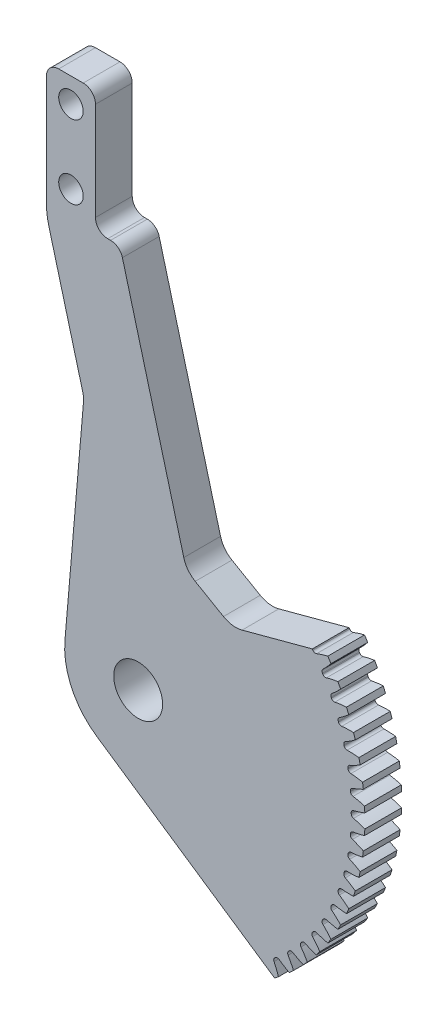
SolidWorks part; units mm, degrees
material "Delrin 2700 NC010, Low Viscosity Acetal Copolymer (SS)"
ref_plane "Front Plane" through (0, 0, 0) normal (0, 0, 1) x (1, 0, 0)
ref_plane "Top Plane" through (0, 0, 0) normal (0, 1, 0) x (1, 0, 0)
ref_plane "Right Plane" through (0, 0, 0) normal (1, 0, 0) x (0, 0, -1)
sketch "Sketch2" plane through (0, 0, 0) normal (0, 0, 1) x (1, 0, 0)
  circle A0 centre (0, 0) radius 60.325
  dimension "D1" = 120.65
extrude "Boss-Extrude2" add sketch "Sketch2" along normal mid plane 9.525
sketch "Sketch3" plane through (0, 0, 4.7625) normal (0, 0, 1) x (1, 0, 0)
  line L0 (0, 0) -> (-57.8242, 215.8028) construction
  line L1 (0, 0) -> (60.325, 0) construction
  line L2 (-14.0744, 58.6602) -> (-23.1191, 92.4153)
  line L3 (-23.1191, 92.4153) -> (-4.7182, 97.3458)
  line L4 (-4.7182, 97.3458) -> (5.2631, 60.095)
  circle A0 centre (0, 0) radius 60.325 construction
  arc A1 (5.2631, 60.095) -> (-14.0744, 58.6602) centre (0, 0) ccw
  dimension "D1" = 105
  dimension "D2" = 19.05
  dimension "D3" = 95.25
  dimension "D4" = 1.5875
extrude "Boss-Extrude3" add sketch "Sketch3" against normal up to surface (9.525 mm away) up to face at (60.325, 0, -4.7625)
sketch "Sketch4" plane through (0, 0, 4.7625) normal (0, 0, 1) x (1, 0, 0)
  line L0 (-4.7182, 97.3458) -> (-23.7682, 97.3458)
  line L1 (-23.7682, 97.3458) -> (-23.7682, 129.0958)
  line L2 (-23.7682, 129.0958) -> (-4.7182, 129.0958)
  line L3 (-4.7182, 129.0958) -> (-4.7182, 97.3458)
  line L4 (5.2631, 60.095) -> (-4.7182, 97.3458) construction
  dimension "D1" = 19.05
  dimension "D2" = 165
  dimension "D3" = 31.75
extrude "Boss-Extrude4" add sketch "Sketch4" against normal up to surface (9.525 mm away) separate body
sketch "Sketch5" plane through (0, 0, 4.7625) normal (0, 0, 1) x (1, 0, 0)
  line L0 (-23.7682, 97.3458) -> (-4.7182, 97.3458) construction
  line L1 (-4.7182, 97.3458) -> (-23.1191, 92.4153) construction
  line L2 (-23.7682, 97.3458) -> (-4.7182, 97.3458)
  line L3 (-4.7182, 97.3458) -> (-23.1191, 92.4153)
  arc A0 (-23.7682, 97.3458) -> (-23.1191, 92.4153) centre (-4.7182, 97.3458) ccw
extrude "Boss-Extrude5" add sketch "Sketch5" against normal up to surface (9.525 mm away)
hole_wizard "1/2 (0.5) Diameter Hole1" positions "Sketch6" profile "Sketch7" hole size "1/2" standard "ANSI Inch" end condition through all
sketch "Sketch6" plane through (0, 0, 4.7625) normal (0, 0, 1) x (1, 0, 0)
  point P0 (0, 0)
sketch "Sketch7" plane through (0, 0, 4.7625) normal (1, 0, 0) x (0, -1, 0)
  line L0 (0, 0) -> (0, 9.525)
  line L1 (0, 9.525) -> (6.3373, 9.525)
  line L2 (6.3373, 9.525) -> (6.3373, 0)
  line L5 (6.3373, 0) -> (0, 0)
  line L11 (0, -6.35) -> (0, 107.95) construction
  dimension "Thru Hole Dia." = 12.6746
  dimension "Thru Hole Depth" = 9.525
sketch "Sketch8" plane through (0, 0, 4.7625) normal (0, 0, 1) x (1, 0, 0)
  line L0 (0, 0) -> (58.2695, 15.6133) construction
  line L1 (-23.1191, 92.4153) -> (-14.0744, 58.6602) construction
  line L2 (24.377, 26.2538) -> (50.3573, 33.2152)
  line L3 (24.377, 26.2538) -> (12.4922, 33.1155)
  line L4 (5.2631, 60.095) -> (12.4922, 33.1155)
  line L5 (5.2631, 60.095) -> (-4.7182, 97.3458) construction
  line L7 (-4.9305, 18.4009) -> (53.339, 34.0141) construction
  arc A0 (-14.0744, 58.6602) -> (5.2631, 60.095) centre (0, 0) ccw construction
  arc A1 (50.3573, 33.2152) -> (5.2631, 60.095) centre (0, 0) ccw
  dimension "D2" = 45
  dimension "D3" = 34.925
  dimension "D1" = 19.05
extrude "Cut-Extrude1" cut sketch "Sketch8" against normal through all
sketch "Sketch9" plane through (0, 0, 4.7625) normal (0, 0, 1) x (1, 0, 0)
  line L0 (-14.0744, 58.6602) -> (-18.9799, 1.6326)
  line L1 (0, 0) -> (58.2695, 15.6133) construction
  line L2 (-23.1191, 92.4153) -> (-14.0744, 58.6602) construction
  line L3 (0, 0) -> (36.7235, -47.859) construction
  line L4 (36.7235, -47.859) -> (-10.6778, -15.7761)
  arc A0 (-18.9799, 1.6326) -> (-10.6778, -15.7761) centre (0, 0) ccw
  arc A1 (-14.0744, 58.6602) -> (50.3573, 33.2152) centre (0, 0) ccw construction
  arc A2 (-14.0744, 58.6602) -> (36.7235, -47.859) centre (0, 0) ccw
  dimension "D1" = 38.1
  dimension "D2" = 67.5
extrude "Cut-Extrude2" cut sketch "Sketch9" against normal through all
sketch "Sketch10" plane through (0, 0, 4.7625) normal (0, 0, 1) x (1, 0, 0)
  line L0 (0, 0) -> (60.325, 0) construction
  line L1 (58.6816, -2.5621) -> (0, 0) construction
  circle A0 centre (0, 0) radius 6.3373 construction
  arc A1 (36.7235, -47.859) -> (50.3573, 33.2152) centre (0, 0) ccw construction
  line B0 (23.419, -49.9795) -> (23.233, -50.0662)
  line B1 (18.9739, -51.8304) -> (18.7811, -51.9006)
  line B2 (14.3844, -53.2869) -> (14.1862, -53.34)
  line B3 (13.4521, -57.1763) -> (12.7131, -57.3452)
  line B4 (12.7131, -57.3452) -> (13.7439, -61.9948)
  line B5 (46.8171, 42.9) -> (43.3058, 39.6825)
  line B6 (43.3058, 39.6825) -> (43.8143, 39.1203)
  line B7 (42.2152, 35.5567) -> (42.3471, 35.3995)
  line B8 (45.1535, 31.7421) -> (45.2712, 31.574)
  line B9 (47.7482, 27.6859) -> (47.8508, 27.5082)
  line B10 (49.9795, 23.419) -> (50.0662, 23.233)
  line B11 (51.8304, 18.9739) -> (51.9006, 18.7811)
  line B12 (53.2869, 14.3844) -> (53.34, 14.1862)
  line B13 (54.3378, 9.6854) -> (54.3734, 9.4833)
  line B14 (54.9751, 4.9127) -> (54.993, 4.7083)
  line B15 (55.1941, 0.1026) -> (55.1941, -0.1026)
  line B16 (54.993, -4.7083) -> (54.9751, -4.9127)
  line B17 (54.3734, -9.4833) -> (54.3378, -9.6854)
  line B18 (53.34, -14.1862) -> (53.2869, -14.3844)
  line B19 (51.9006, -18.7811) -> (51.8304, -18.9739)
  line B20 (50.0662, -23.233) -> (49.9795, -23.419)
  line B21 (47.8508, -27.5082) -> (47.7482, -27.6859)
  line B22 (45.2712, -31.574) -> (45.1535, -31.7421)
  line B23 (42.3471, -35.3995) -> (42.2152, -35.5567)
  line B24 (39.1007, -38.9556) -> (38.9556, -39.1007)
  line B25 (35.5567, -42.2152) -> (35.3995, -42.3471)
  line B26 (31.7421, -45.1535) -> (31.574, -45.2712)
  line B27 (27.6859, -47.7482) -> (27.5082, -47.8508)
  circle B28 centre (0, 0) radius 7.9375 construction
  arc B29 (26.4473, -52.4465) -> (27.7921, -51.7464) centre (0, 0) ccw
  arc B30 (24.374, -50.2004) -> (26.4473, -52.4465) centre (42.0357, -35.9774) ccw
  arc B31 (24.374, -50.2004) -> (23.419, -49.9795) centre (23.7558, -50.6982) ccw
  arc B32 (23.233, -50.0662) -> (22.7884, -50.9398) centre (23.5672, -50.7862) ccw
  arc B33 (23.1763, -53.9718) -> (22.7884, -50.9398) centre (0.5402, -55.327) ccw
  arc B34 (21.7757, -54.5519) -> (23.1763, -53.9718) centre (0, 0) ccw
  arc B35 (19.906, -52.1337) -> (21.7757, -54.5519) centre (38.7401, -39.5041) ccw
  arc B36 (19.906, -52.1337) -> (18.9739, -51.8304) centre (19.2468, -52.5758) ccw
  arc B37 (18.7811, -51.9006) -> (18.262, -52.7321) centre (19.0512, -52.647) ccw
  arc B38 (18.3842, -55.7863) -> (18.262, -52.7321) centre (-4.2839, -55.1635) ccw
  arc B39 (16.9383, -56.2422) -> (18.3842, -55.7863) centre (0, 0) ccw
  arc B40 (15.2865, -53.6702) -> (16.9383, -56.2422) centre (35.1497, -42.7302) ccw
  arc B41 (15.2865, -53.6702) -> (14.3844, -53.2869) centre (14.5913, -54.0532) ccw
  arc B42 (14.1862, -53.34) -> (13.5966, -54.1231) centre (14.3902, -54.1071) ccw
  arc B43 (13.4521, -57.1763) -> (13.5966, -54.1231) centre (-9.0754, -54.5803) ccw
  arc B44 (13.7439, -61.9948) -> (46.8171, 42.9) centre (0, 0) ccw
  arc B45 (42.1814, 36.5363) -> (43.8143, 39.1203) centre (23.8718, 49.915) ccw
  arc B46 (42.1814, 36.5363) -> (42.2152, 35.5567) centre (42.8223, 36.068) ccw
  arc B47 (42.3471, 35.3995) -> (43.306, 35.1961) centre (42.9561, 35.9086) ccw
  arc B48 (46.1343, 36.3555) -> (43.306, 35.1961) centre (53.302, 14.8415) ccw
  arc B49 (47.0572, 35.1528) -> (46.1343, 36.3555) centre (0, 0) ccw
  arc B50 (45.2052, 32.7209) -> (47.0572, 35.1528) centre (28.1314, 47.6445) ccw
  arc B51 (45.2052, 32.7209) -> (45.1535, 31.7421) centre (45.8029, 32.1986) ccw
  arc B52 (45.2712, 31.574) -> (46.2087, 31.2878) centre (45.9223, 32.0281) ccw
  arc B53 (49.1273, 32.1963) -> (46.2087, 31.2878) centre (54.3926, 10.1395) ccw
  arc B54 (49.9419, 30.9177) -> (49.1273, 32.1963) centre (0, 0) ccw
  arc B55 (47.885, 28.6565) -> (49.9419, 30.9177) centre (32.1768, 45.0114) ccw
  arc B56 (47.885, 28.6565) -> (47.7482, 27.6859) centre (48.4349, 28.0841) ccw
  arc B57 (47.8508, 27.5082) -> (48.7598, 27.1414) centre (48.5389, 27.9038) ccw
  arc B58 (51.7464, 27.7921) -> (48.7598, 27.1414) centre (55.0694, 5.3602) ccw
  arc B59 (52.4465, 26.4473) -> (51.7464, 27.7921) centre (0, 0) ccw
  arc B60 (50.2004, 24.374) -> (52.4465, 26.4473) centre (35.9774, 42.0357) ccw
  arc B61 (50.2004, 24.374) -> (49.9795, 23.419) centre (50.6982, 23.7558) ccw
  arc B62 (50.0662, 23.233) -> (50.9398, 22.7884) centre (50.7862, 23.5672) ccw
  arc B63 (53.9718, 23.1763) -> (50.9398, 22.7884) centre (55.327, 0.5402) ccw
  arc B64 (54.5519, 21.7757) -> (53.9718, 23.1763) centre (0, 0) ccw
  arc B65 (52.1337, 19.906) -> (54.5519, 21.7757) centre (39.5041, 38.7401) ccw
  arc B66 (52.1337, 19.906) -> (51.8304, 18.9739) centre (52.5758, 19.2468) ccw
  arc B67 (51.9006, 18.7811) -> (52.7321, 18.262) centre (52.647, 19.0512) ccw
  arc B68 (55.7863, 18.3842) -> (52.7321, 18.262) centre (55.1635, -4.2839) ccw
  arc B69 (56.2422, 16.9383) -> (55.7863, 18.3842) centre (0, 0) ccw
  arc B70 (53.6702, 15.2865) -> (56.2422, 16.9383) centre (42.7302, 35.1497) ccw
  arc B71 (53.6702, 15.2865) -> (53.2869, 14.3844) centre (54.0532, 14.5913) ccw
  arc B72 (53.34, 14.1862) -> (54.1231, 13.5966) centre (54.1071, 14.3902) ccw
  arc B73 (57.1763, 13.4521) -> (54.1231, 13.5966) centre (54.5803, -9.0754) ccw
  arc B74 (57.5045, 11.972) -> (57.1763, 13.4521) centre (0, 0) ccw
  arc B75 (54.7983, 10.5507) -> (57.5045, 11.972) centre (45.6311, 31.2917) ccw
  arc B76 (54.7983, 10.5507) -> (54.3378, 9.6854) centre (55.1192, 9.8247) ccw
  arc B77 (54.3734, 9.4833) -> (55.1021, 8.8277) centre (55.1553, 9.6197) ccw
  arc B78 (58.1312, 8.4177) -> (55.1021, 8.8277) centre (53.5816, -13.7979) ccw
  arc B79 (58.3291, 6.9146) -> (58.1312, 8.4177) centre (0, 0) ccw
  arc B80 (55.5093, 5.7346) -> (58.3291, 6.9146) centre (48.1847, 27.1956) ccw
  arc B81 (55.5093, 5.7346) -> (54.9751, 4.9127) centre (55.7657, 4.9834) ccw
  arc B82 (54.993, 4.7083) -> (55.6618, 3.9917) centre (55.7839, 4.776) ccw
  arc B83 (58.6436, 3.3192) -> (55.6618, 3.9917) centre (52.1751, -18.4153) ccw
  arc B84 (58.7098, 1.8046) -> (58.6436, 3.3192) centre (0, 0) ccw
  arc B85 (55.7979, 0.8748) -> (58.7098, 1.8046) centre (50.3716, 22.8926) ccw
  arc B86 (55.7979, 0.8748) -> (55.1941, 0.1026) centre (55.9879, 0.1041) ccw
  arc B87 (55.1941, -0.1026) -> (55.7979, -0.8748) centre (55.9879, -0.1041) ccw
  arc B88 (58.7098, -1.8046) -> (55.7979, -0.8748) centre (50.3716, -22.8926) ccw
  arc B89 (58.6436, -3.3192) -> (58.7098, -1.8046) centre (0, 0) ccw
  arc B90 (55.6618, -3.9917) -> (58.6436, -3.3192) centre (52.1751, 18.4153) ccw
  arc B91 (55.6618, -3.9917) -> (54.993, -4.7083) centre (55.7839, -4.776) ccw
  arc B92 (54.9751, -4.9127) -> (55.5093, -5.7346) centre (55.7657, -4.9834) ccw
  arc B93 (58.3291, -6.9146) -> (55.5093, -5.7346) centre (48.1847, -27.1956) ccw
  arc B94 (58.1312, -8.4177) -> (58.3291, -6.9146) centre (0, 0) ccw
  arc B95 (55.1021, -8.8277) -> (58.1312, -8.4177) centre (53.5816, 13.7979) ccw
  arc B96 (55.1021, -8.8277) -> (54.3734, -9.4833) centre (55.1553, -9.6197) ccw
  arc B97 (54.3378, -9.6854) -> (54.7983, -10.5507) centre (55.1192, -9.8247) ccw
  arc B98 (57.5045, -11.972) -> (54.7983, -10.5507) centre (45.6311, -31.2917) ccw
  arc B99 (57.1763, -13.4521) -> (57.5045, -11.972) centre (0, 0) ccw
  arc B100 (54.1231, -13.5966) -> (57.1763, -13.4521) centre (54.5803, 9.0754) ccw
  arc B101 (54.1231, -13.5966) -> (53.34, -14.1862) centre (54.1071, -14.3902) ccw
  arc B102 (53.2869, -14.3844) -> (53.6702, -15.2865) centre (54.0532, -14.5913) ccw
  arc B103 (56.2422, -16.9383) -> (53.6702, -15.2865) centre (42.7302, -35.1497) ccw
  arc B104 (55.7863, -18.3842) -> (56.2422, -16.9383) centre (0, 0) ccw
  arc B105 (52.7321, -18.262) -> (55.7863, -18.3842) centre (55.1635, 4.2839) ccw
  arc B106 (52.7321, -18.262) -> (51.9006, -18.7811) centre (52.647, -19.0512) ccw
  arc B107 (51.8304, -18.9739) -> (52.1337, -19.906) centre (52.5758, -19.2468) ccw
  arc B108 (54.5519, -21.7757) -> (52.1337, -19.906) centre (39.5041, -38.7401) ccw
  arc B109 (53.9718, -23.1763) -> (54.5519, -21.7757) centre (0, 0) ccw
  arc B110 (50.9398, -22.7884) -> (53.9718, -23.1763) centre (55.327, -0.5402) ccw
  arc B111 (50.9398, -22.7884) -> (50.0662, -23.233) centre (50.7862, -23.5672) ccw
  arc B112 (49.9795, -23.419) -> (50.2004, -24.374) centre (50.6982, -23.7558) ccw
  arc B113 (52.4465, -26.4473) -> (50.2004, -24.374) centre (35.9774, -42.0357) ccw
  arc B114 (51.7464, -27.7921) -> (52.4465, -26.4473) centre (0, 0) ccw
  arc B115 (48.7598, -27.1414) -> (51.7464, -27.7921) centre (55.0694, -5.3602) ccw
  arc B116 (48.7598, -27.1414) -> (47.8508, -27.5082) centre (48.5389, -27.9038) ccw
  arc B117 (47.7482, -27.6859) -> (47.885, -28.6565) centre (48.4349, -28.0841) ccw
  arc B118 (49.9419, -30.9177) -> (47.885, -28.6565) centre (32.1768, -45.0114) ccw
  arc B119 (49.1273, -32.1963) -> (49.9419, -30.9177) centre (0, 0) ccw
  arc B120 (46.2087, -31.2878) -> (49.1273, -32.1963) centre (54.3926, -10.1395) ccw
  arc B121 (46.2087, -31.2878) -> (45.2712, -31.574) centre (45.9223, -32.0281) ccw
  arc B122 (45.1535, -31.7421) -> (45.2052, -32.7209) centre (45.8029, -32.1986) ccw
  arc B123 (47.0572, -35.1528) -> (45.2052, -32.7209) centre (28.1314, -47.6445) ccw
  arc B124 (46.1343, -36.3555) -> (47.0572, -35.1528) centre (0, 0) ccw
  arc B125 (43.306, -35.1961) -> (46.1343, -36.3555) centre (53.302, -14.8415) ccw
  arc B126 (43.306, -35.1961) -> (42.3471, -35.3995) centre (42.9561, -35.9086) ccw
  arc B127 (42.2152, -35.5567) -> (42.1814, -36.5363) centre (42.8223, -36.068) ccw
  arc B128 (43.8143, -39.1203) -> (42.1814, -36.5363) centre (23.8718, -49.915) ccw
  arc B129 (42.7901, -40.238) -> (43.8143, -39.1203) centre (0, 0) ccw
  arc B130 (40.0736, -38.8365) -> (42.7901, -40.238) centre (51.8056, -19.4306) ccw
  arc B131 (40.0736, -38.8365) -> (39.1007, -38.9556) centre (39.663, -39.5158) ccw
  arc B132 (38.9556, -39.1007) -> (38.8365, -40.0736) centre (39.5158, -39.663) ccw
  arc B133 (40.238, -42.7901) -> (38.8365, -40.0736) centre (19.4306, -51.8056) ccw
  arc B134 (39.1203, -43.8143) -> (40.238, -42.7901) centre (0, 0) ccw
  arc B135 (36.5363, -42.1814) -> (39.1203, -43.8143) centre (49.915, -23.8718) ccw
  arc B136 (36.5363, -42.1814) -> (35.5567, -42.2152) centre (36.068, -42.8223) ccw
  arc B137 (35.3995, -42.3471) -> (35.1961, -43.306) centre (35.9086, -42.9561) ccw
  arc B138 (36.3555, -46.1343) -> (35.1961, -43.306) centre (14.8415, -53.302) ccw
  arc B139 (35.1528, -47.0572) -> (36.3555, -46.1343) centre (0, 0) ccw
  arc B140 (32.7209, -45.2052) -> (35.1528, -47.0572) centre (47.6445, -28.1314) ccw
  arc B141 (32.7209, -45.2052) -> (31.7421, -45.1535) centre (32.1986, -45.8029) ccw
  arc B142 (31.574, -45.2712) -> (31.2878, -46.2087) centre (32.0281, -45.9223) ccw
  arc B143 (32.1963, -49.1273) -> (31.2878, -46.2087) centre (10.1395, -54.3926) ccw
  arc B144 (30.9177, -49.9419) -> (32.1963, -49.1273) centre (0, 0) ccw
  arc B145 (28.6565, -47.885) -> (30.9177, -49.9419) centre (45.0114, -32.1768) ccw
  arc B146 (28.6565, -47.885) -> (27.6859, -47.7482) centre (28.0841, -48.4349) ccw
  arc B147 (27.5082, -47.8508) -> (27.1414, -48.7598) centre (27.9038, -48.5389) ccw
  arc B148 (27.7921, -51.7464) -> (27.1414, -48.7598) centre (5.3602, -55.0694) ccw
  dimension "D1" = 2.5
sketch_block_instance "Block1-1"
sketch_block "Block1"
extrude "Cut-Extrude3" cut sketch "Sketch10" against normal blind 12.7
sketch "Sketch15" plane through (0, 0, 4.7625) normal (0, 0, 1) x (1, 0, 0)
  line L0 (-4.7182, 129.0958) -> (-23.7682, 129.0958) construction
  line L1 (-11.0682, 129.0958) -> (-4.7182, 129.0958)
  line L2 (-11.0682, 129.0958) -> (-11.0682, 97.3458)
  line L3 (-11.0682, 97.3458) -> (-4.7182, 97.3458)
  line L4 (-4.7182, 129.0958) -> (-4.7182, 97.3458)
  line L5 (12.4922, 33.1155) -> (-4.7182, 97.3458) construction
  dimension "D1" = 12.7
  dimension "D2" = 31.75
extrude "Cut-Extrude6" cut sketch "Sketch15" against normal through all
hole_wizard "1/4 (0.25) Diameter Hole1" positions "Sketch11" profile "Sketch12" hole size "1/4" standard "ANSI Inch" end condition through all
sketch "Sketch11" plane through (0, 0, 4.7625) normal (0, 0, 1) x (1, 0, 0)
  line L0 (-17.4182, 129.0958) -> (-17.4182, 95.6738) construction
  line L4 (-23.6052, 94.8593) -> (-4.7182, 97.3458) construction
  line L8 (-11.0682, 129.0958) -> (-23.7682, 129.0958) construction
  line L9 (-11.0682, 129.0958) -> (-11.0682, 97.3458) construction
  arc A0 (-23.7682, 97.3458) -> (-23.1191, 92.4153) centre (-4.7182, 97.3458) ccw construction
  point P0 (-17.4182, 122.7458)
  point P2 (-17.4182, 103.6958)
  dimension "D1" = 19.05
  dimension "D2" = 6.35
  dimension "D3" = 6.35
sketch "Sketch12" plane through (-17.4182, 122.7458, 4.7625) normal (1, 0, 0) x (0, -1, 0)
  line L0 (0, 0) -> (0, 9.525)
  line L1 (0, 9.525) -> (3.175, 9.525)
  line L2 (3.175, 9.525) -> (3.175, 0)
  line L5 (3.175, 0) -> (0, 0)
  line L11 (0, -6.35) -> (0, 107.95) construction
  dimension "Thru Hole Dia." = 6.35
  dimension "Thru Hole Depth" = 9.525
fillet "Fillet1" radius 6.35 3 edges at (24.377, 26.2538, 0) (12.4922, 33.1155, 0) (-14.0744, 58.6602, 0)
fillet "Fillet3" radius 3.175 4 edges at (-11.0682, 97.3458, 0) (-11.0682, 129.0958, 0) (-23.7682, 129.0958, 0) (-4.7182, 97.3458, 0)
sketch "Sketch13" plane through (0, 0, -4.7625) normal (0, 0, 1) x (1, 0, 0)
  line L0 (0, 0) -> (82.2868, 0) construction
  line L1 (25.4, 0) -> (50.8, 0) construction
  line L2 (25.4, 1.6002) -> (50.8, 1.6002)
  line L3 (25.4, -1.6002) -> (50.8, -1.6002)
  arc A0 (25.4, 1.6002) -> (25.4, -1.6002) centre (25.4, 0) ccw
  arc A1 (50.8, -1.6002) -> (50.8, 1.6002) centre (50.8, 0) ccw
  circle A2 centre (0, 0) radius 6.3373 construction
  point P5 (38.1, 0)
  dimension "D1" = 1.6002
  dimension "D3" = 25.4
  dimension "D2" = 25.4
extrude "Cut-Extrude4" cut sketch "Sketch13" along normal blind 1.5875
sketch "Sketch14" plane through (0, 0, -4.7625) normal (0, 0, 1) x (1, 0, 0)
  text T0 "<b>R</b>" font "Century Gothic" height 19.05
  dimension "D1" = 44.45
  dimension "D2" = 6.35
extrude "Cut-Extrude5" cut sketch "Sketch14" along normal blind 1.5875
fillet "Fillet2" radius 0.7937 12 edges at (36.2225, 15.1423, -3.9688) (29.7962, 20.3017, -3.9688) (33.8603, 25.1443, -3.9688) (38.1076, 25.4, -3.9688) (29.5519, 6.35, -3.9688) (39.5654, 23.2019, -3.9687) (39.5654, 17.3366, -3.9687) (42.0077, 25.4, -3.9688) (32.2423, 6.35, -3.9688) (38.9128, 15.1423, -3.9688) (39.5654, 6.35, -3.9688) (42.0077, 6.35, -3.9688)
equation "\"D1@Sketch2\"=2.375*2"
equation "\"D1@Sketch8\"=0.8125in-.015625*4"
equation "\"D2@Sketch9\"=80.00deg-2.5-10"
equation "\"D3@Sketch4\"=1.250in+.125-.125"
